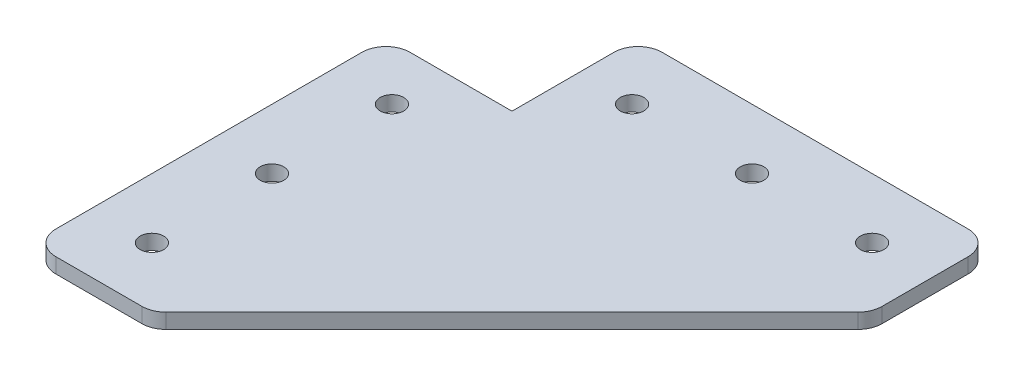
SolidWorks part; units mm, degrees
material "6061-T6 (SS)"
ref_plane "Front Plane" through (0, 0, 0) normal (0, 0, 1) x (1, 0, 0)
ref_plane "Top Plane" through (0, 0, 0) normal (0, 1, 0) x (1, 0, 0)
ref_plane "Right Plane" through (0, 0, 0) normal (1, 0, 0) x (0, 0, -1)
sketch "Sketch1" plane through (0, 0, 0) normal (0, 1, 0) x (1, 0, 0)
  line L0 (0, 0) -> (0, 101.6)
  line L1 (0, 101.6) -> (101.6, 101.6)
  line L3 (0, 0) -> (25.4, 0)
  line L4 (25.4, 0) -> (101.6, 76.2)
  line L5 (101.6, 76.2) -> (101.6, 101.6)
  dimension "D1" = 101.6
  dimension "D2" = 101.6
  dimension "D3" = 25.4
  dimension "D4" = 25.4
extrude "Boss-Extrude1" add sketch "Sketch1" along normal blind 3.175
sketch "Sketch2" plane through (0, 3.175, 0) normal (0, 1, 0) x (1, 0, 0)
  line L0 (101.6, 101.6) -> (0, 101.6) construction
  line L1 (0, 101.6) -> (0, 0) construction
  circle A0 centre (12.7, 88.9) radius 2.4892
  circle A1 centre (38.1, 88.9) radius 2.4892
  circle A2 centre (63.5, 88.9) radius 2.4892
  circle A3 centre (88.9, 88.9) radius 2.4892
  circle A4 centre (12.7, 63.5) radius 2.4892
  circle A5 centre (12.7, 38.1) radius 2.4892
  circle A6 centre (12.7, 12.7) radius 2.4892
  point P18 (0, 0)
  point P19 (0, 0)
  point P20 (0, 0)
  dimension "D1" = 25.4
  dimension "D2" = 12.7
  dimension "D3" = 25.4
  dimension "D4" = 25.4
  dimension "D5" = 25.4
  dimension "D6" = 25.4
  dimension "D7" = 25.4
  dimension "D8" = 12.7
  dimension "D9" = 4.9784
extrude "Cut-Extrude1" cut sketch "Sketch2" against normal through all
sketch "Sketch3" plane through (0, 3.175, 0) normal (0, 1, 0) x (1, 0, 0)
  line L1 (0, 101.6) -> (26.67, 101.6)
  line L2 (0, 101.6) -> (0, 74.93)
  line L3 (0, 74.93) -> (26.67, 74.93)
  line L4 (26.67, 101.6) -> (26.67, 74.93)
  dimension "D1" = 26.67
extrude "Cut-Extrude2" cut sketch "Sketch3" against normal through all
fillet "Fillet1" radius 5.08 6 edges at (0, 1.5875, 0) (25.4, 1.5875, 0) (101.6, 1.5875, -76.2) (101.6, 1.5875, -101.6) (26.67, 1.5875, -101.6) (0, 1.5875, -74.93)
